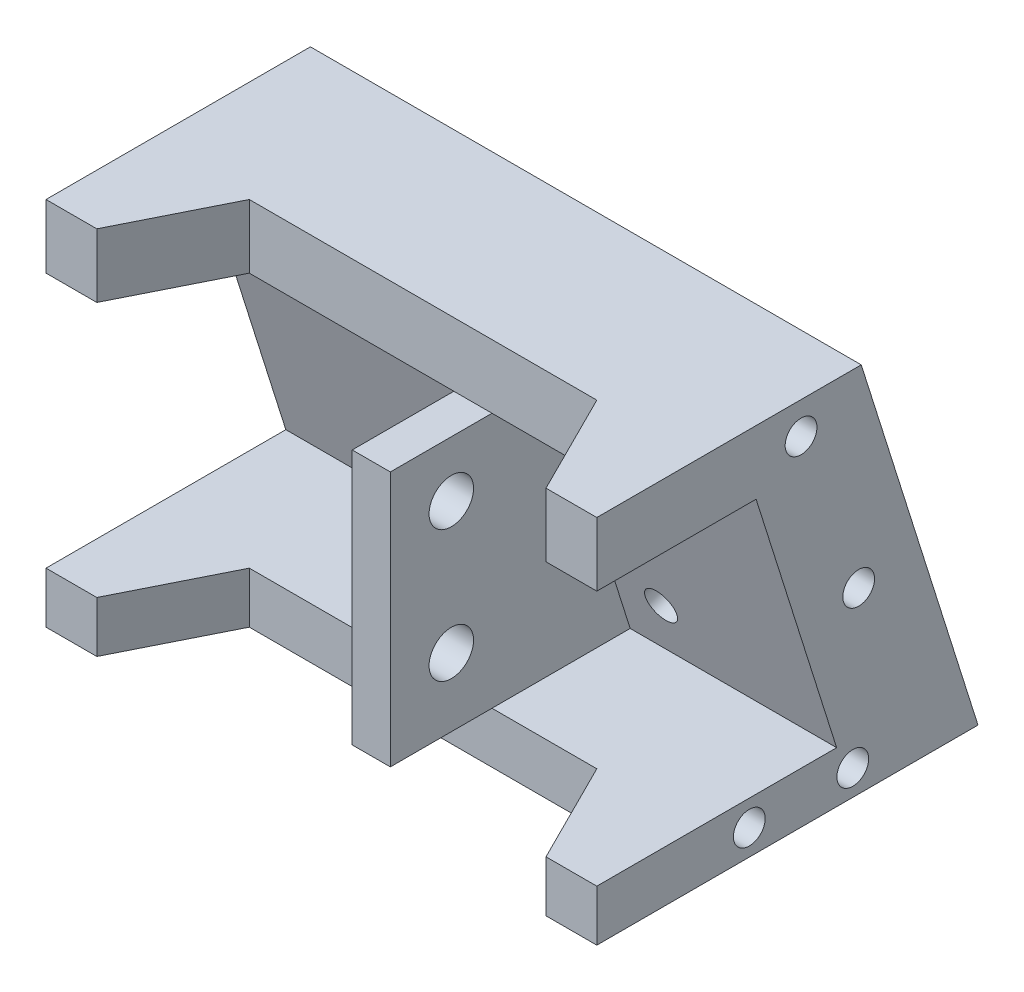
SolidWorks part; units mm, degrees
ref_plane "Front Plane" through (0, 0, 0) normal (0, 0, 1) x (1, 0, 0)
ref_plane "Top Plane" through (0, 0, 0) normal (0, 1, 0) x (1, 0, 0)
ref_plane "Right Plane" through (0, 0, 0) normal (1, 0, 0) x (0, 0, -1)
sketch "Sketch1" plane through (0, 0, 0) normal (0, 0, 1) x (1, 0, 0)
  line L1 (-54.239, -0.1442) -> (-10.889, -0.1442)
  line L2 (-54.239, -0.1442) -> (-54.239, -29.2942)
  line L3 (-54.239, -29.2942) -> (-10.889, -29.2942)
  line L4 (-10.889, -0.1442) -> (-10.889, -29.2942)
extrude "Boss-Extrude1" add sketch "Sketch1" against normal blind 30
sketch "Sketch9" plane through (0, -29.2942, 0) normal (0, -1, 0) x (1, 0, 0)
  line L0 (-10.889, 0) -> (-18.889, 0) construction
  line L1 (-54.239, 0) -> (-10.889, 0) construction
  line L2 (-18.889, 0) -> (-14.889, 0) construction
  line L3 (-14.889, 0) -> (-14.889, -8) construction
  line L5 (-18.889, 0) -> (-18.889, -8) construction
  line L6 (-18.889, -8) -> (-14.889, -8) construction
  line L7 (-14.889, -8) -> (-54.239, -8) construction
  line L8 (-54.239, -30) -> (-54.239, 0) construction
  line L9 (-54.239, -8) -> (-54.239, 0) construction
  line L10 (-54.239, 0) -> (-46.239, 0) construction
  line L11 (-46.239, 0) -> (-46.239, -8) construction
  line L12 (-46.239, -8) -> (-54.239, -8) construction
  line L13 (-54.239, -8) -> (-50.239, -8) construction
  line L14 (-50.239, -8) -> (-50.239, 0) construction
  line L15 (-14.889, 0) -> (-18.889, -8)
  line L16 (-18.889, -8) -> (-46.239, -8)
  line L17 (-46.239, -8) -> (-50.239, 0)
  line L18 (-50.239, 0) -> (-14.889, 0)
extrude "Cut-Extrude6" cut sketch "Sketch9" against normal blind 28.13
sketch "Sketch11" plane through (-54.239, 0, 0) normal (-1, 0, 0) x (0, 0, 1)
  line L0 (0, -29.2942) -> (0, -25.2705) construction
  line L1 (0, -0.1442) -> (0, -29.2942) construction
  line L2 (0, -25.2705) -> (0, -0.1442) construction
  line L3 (0, -0.1442) -> (0, -5.1642) construction
  line L4 (0, -5.1642) -> (0, -25.2705) construction
  line L7 (-30, -0.1442) -> (-30, -29.2942) construction
  line L8 (-30, -5.1642) -> (-30, -29.2942) construction
  line L10 (-30, -29.2942) -> (-30, -25.2705) construction
  line L12 (0, -5.1642) -> (0, -25.2705) construction
  line L13 (-30, -25.2705) -> (-18.8756, -25.2705) construction
  line L14 (0, -25.2705) -> (-18.8756, -25.2705) construction
  line L15 (-18.8756, -25.2705) -> (-18.8756, -5.1642) construction
  line L16 (-18.8756, -5.1642) -> (0, -5.1642) construction
  line L17 (0, -5.1642) -> (0, -25.2705) construction
  line L18 (0, -25.2705) -> (-18.8756, -25.2705)
  line L19 (-18.8756, -25.2705) -> (-18.8756, -5.1642)
  line L20 (-18.8756, -5.1642) -> (0, -5.1642)
  line L21 (0, -5.1642) -> (0, -25.2705)
extrude "Cut-Extrude8" cut sketch "Sketch11" against normal blind 50
sketch "Sketch14" plane through (0, 0, -30) normal (0, 0, -1) x (-1, 0, 0)
  line L0 (10.889, -29.2942) -> (34.989, -29.2942) construction
  line L1 (10.889, -0.1442) -> (34.989, -0.1442) construction
  line L6 (34.989, -29.2942) -> (34.989, -0.1442) construction
  line L7 (34.989, -0.1442) -> (37.989, -0.1442) construction
  line L8 (37.989, -0.1442) -> (37.989, -29.2942) construction
  line L9 (37.989, -29.2942) -> (34.989, -29.2942) construction
  line L10 (34.989, -29.2942) -> (37.989, -29.2942)
  line L11 (37.989, -29.2942) -> (37.989, -0.1442)
  line L12 (37.989, -0.1442) -> (34.989, -0.1442)
  line L13 (34.989, -0.1442) -> (34.989, -29.2942)
extrude "Boss-Extrude5" add sketch "Sketch14" against normal blind 30
sketch "Sketch15" plane through (-37.989, 0, 0) normal (-1, 0, 0) x (0, 0, 1)
  line L0 (-8, -25.2705) -> (0, -25.2705) construction
  line L1 (0, -29.2942) -> (0, -1.1642) construction
  line L2 (0, -25.2705) -> (0, -29.2942) construction
  line L3 (0, -29.2942) -> (-8, -29.2942) construction
  line L4 (-8, -29.2942) -> (-8, -25.2705) construction
  line L5 (-8, -25.2705) -> (0, -25.2705)
  line L6 (0, -25.2705) -> (0, -29.2942)
  line L7 (0, -29.2942) -> (-8, -29.2942)
  line L8 (-8, -29.2942) -> (-8, -25.2705)
extrude "Cut-Extrude10" cut sketch "Sketch15" against normal blind 5
sketch "Sketch16" plane through (-37.989, 0, 0) normal (-1, 0, 0) x (0, 0, 1)
  line L0 (-8, -1.1642) -> (0, -1.1642) construction
  line L1 (0, -25.2705) -> (0, -1.1642) construction
  line L3 (0, -1.1642) -> (-8, -1.1642) construction
  line L4 (-8, -1.1642) -> (-8, -5.1642) construction
  line L5 (-8, -5.1642) -> (0, -5.1642) construction
  line L6 (0, -5.1642) -> (0, -1.1642) construction
  line L7 (0, -1.1642) -> (0, -5.1642)
  line L8 (0, -5.1642) -> (-8, -5.1642)
  line L9 (-8, -5.1642) -> (-8, -1.1642)
  line L10 (-8, -1.1642) -> (0, -1.1642)
extrude "Cut-Extrude11" cut sketch "Sketch16" against normal blind 5
sketch "Sketch17" plane through (-37.989, 0, 0) normal (-1, 0, 0) x (0, 0, 1)
  line L0 (0, -25.2705) -> (0, -19.8992) construction
  line L2 (0, -19.8992) -> (-4.8, -19.8992) construction
  line L3 (0, -5.1642) -> (0, -9.5492) construction
  line L4 (0, -9.5492) -> (-4.8, -9.5492) construction
  line L5 (-4.8, -9.5492) -> (-4.8, -19.8992) construction
  circle A0 centre (-4.8, -19.8992) radius 1.75
  circle A1 centre (-4.8, -9.5492) radius 1.75
extrude "Cut-Extrude12" cut sketch "Sketch17" against normal blind 5
sketch "Sketch20" plane through (-54.239, 0, 0) normal (-1, 0, 0) x (0, 0, 1)
  line L0 (-30, -0.1442) -> (-30, -29.2942) construction
  line L1 (-30, -29.2942) -> (-20.81, -0.1442) construction
  line L2 (-30, -0.1442) -> (0, -0.1442) construction
  line L3 (-20.81, -0.1442) -> (-30, -0.1442) construction
  line L4 (-30, -29.2942) -> (-30, -0.1442)
  line L5 (-30, -0.1442) -> (-20.81, -0.1442)
  line L6 (-20.81, -0.1442) -> (-30, -29.2942)
extrude "Cut-Extrude14" cut sketch "Sketch20" against normal blind 50
sketch "Sketch30" plane through (-54.239, 0, 0) normal (-1, 0, 0) x (0, 0, 1)
  line L0 (-25.1458, -29.2942) -> (-7, -29.2942) construction
  line L1 (-7, -29.2942) -> (-12.0012, -29.2942) construction
  line L2 (-12.0012, -29.2942) -> (-25.1458, -29.2942) construction
  line L3 (-25.1458, -29.2942) -> (-20.1458, -29.2942) construction
  line L4 (-7, -29.2942) -> (-7, -27.2842) construction
  line L5 (-7, -27.2842) -> (-20.1458, -27.2842) construction
  line L6 (-20.1458, -27.2842) -> (-7, -27.2842) construction
  line L7 (-7, -27.2842) -> (-12.0012, -27.2842) construction
  line L8 (-20.1458, -29.2942) -> (-20.1458, -27.2842) construction
  line L10 (0, -25.2705) -> (0, -29.2942) construction
  line L11 (0, -27.2823) -> (0, -29.2942) construction
  line L12 (0, -29.2942) -> (0, -27.2823) construction
  line L13 (0, -27.2823) -> (-7, -27.2842) construction
  line L14 (-7, -27.2842) -> (-7, -29.2942) construction
  line L15 (-7, -29.2942) -> (-7, -27.2842) construction
  line L16 (-7, -27.2842) -> (-12.0012, -27.2842) construction
  line L17 (-12.0012, -27.2842) -> (-12.0012, -29.2942) construction
  line L18 (-12.0012, -29.2942) -> (-12.0012, -27.2842) construction
  circle A0 centre (-12.0012, -27.2842) radius 1.25
  circle A1 centre (-20.1458, -27.2842) radius 1.25
extrude "Cut-Extrude23" cut sketch "Sketch30" against normal blind 45
sketch "Sketch31" plane through (-54.239, 0, 0) normal (-1, 0, 0) x (0, 0, 1)
  line L0 (-20.1458, -27.2842) -> (-12.0012, -27.2842) construction
  line L1 (-12.0012, -27.2842) -> (-16.0735, -27.2842) construction
  line L2 (-16.0735, -27.2842) -> (-16.0735, -0.1442) construction
  line L3 (-16.0735, -5.1642) -> (-16.0735, -0.1442) construction
  line L4 (-16.0735, -0.1442) -> (-16.0735, -5.1642) construction
  line L5 (0, -5.1642) -> (-18.8756, -5.1642) construction
  line L6 (-16.0735, -5.1642) -> (-16.0735, -2.6542) construction
  line L7 (-20.81, -0.1442) -> (0, -0.1442) construction
  line L8 (-16.0735, -0.1442) -> (-16.0735, -2.6542) construction
  line L9 (-16.0735, -2.6542) -> (-16.0735, -0.1442) construction
  line L10 (-16.0735, -0.1442) -> (-16.0735, -2.6542) construction
  circle A0 centre (-16.0735, -2.6542) radius 1.25
extrude "Cut-Extrude24" cut sketch "Sketch31" against normal blind 50
sketch "Sketch32" plane through (-54.239, 0, 0) normal (-1, 0, 0) x (0, 0, 1)
  line L0 (-25.1427, -28.8998) -> (-22.7033, -1.5865) construction
  line L1 (-22.7033, -1.5865) -> (-23.923, -15.2431) construction
  line L2 (-23.923, -15.2431) -> (-20.6098, -15.2431) construction
  circle A0 centre (-20.6098, -15.2431) radius 1.25
extrude "Cut-Extrude25" cut sketch "Sketch32" against normal blind 50
sketch "Sketch56" plane through (0, -1.1642, 0) normal (0, -1, 0) x (1, 0, 0)
  line L0 (-14.889, 0) -> (-18.889, -8)
  line L1 (-18.889, -8) -> (-46.239, -8)
  line L2 (-46.239, -8) -> (-50.239, 0)
  line L3 (-50.239, 0) -> (-14.889, 0)
extrude "Cut-Extrude29" cut sketch "Sketch56" against normal blind 5
sketch "Sketch68" plane through (-34.989, 0, 0) normal (1, 0, 0) x (0, 0, -1)
  line L0 (18.8756, -5.1642) -> (12.5356, -5.1642)
  line L1 (8, -5.1642) -> (18.8756, -5.1642) construction
  line L2 (12.5356, -5.1642) -> (18.8756, -25.2705)
  line L4 (18.8756, -5.1642) -> (18.8756, -25.2705)
extrude "Boss-Extrude13" add sketch "Sketch68" along normal blind 24.1
sketch "Sketch73" plane through (-37.989, 0, 0) normal (-1, 0, 0) x (0, 0, 1)
  line L0 (-18.8756, -5.1642) -> (-12.5356, -5.1642)
  line L1 (-12.5356, -5.1642) -> (-18.8756, -25.2705)
  line L2 (-18.8756, -25.2705) -> (-18.8756, -5.1642)
extrude "Boss-Extrude14" add sketch "Sketch73" along normal blind 16.25
mirror "Mirror1" about plane through (-10.889, -0.1442, -30) normal (1, 0, 0) of bodies 154 157
delete or keep bodies "Body-Delete/Keep 1" type delete bodies bodies 154
sketch "Sketch74" plane through (0, 5.9545, -18.8873) normal (0, 0.3007, -0.9537) x (-1, 0, 0)
  circle A0 centre (-19.9192, -25.5324) radius 1.25
  circle A1 centre (-1.5382, -25.5324) radius 1.25
  circle A2 centre (-1.5382, -14.2689) radius 1.25
  circle A3 centre (-19.9192, -14.2689) radius 1.25
extrude "Cut-Extrude30" cut sketch "Sketch74" against normal blind 10
